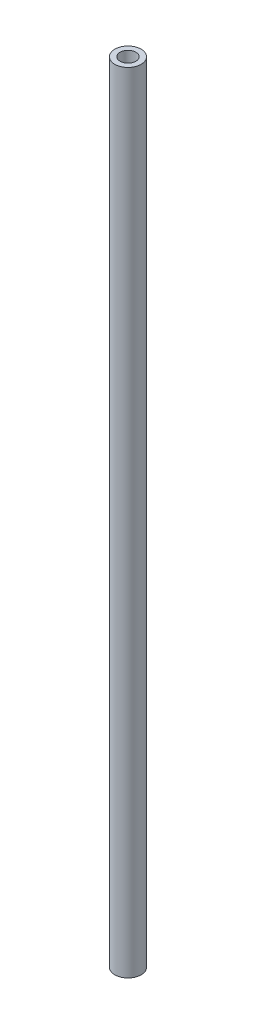
SolidWorks part; units mm, degrees
ref_plane "前视基准面" through (0, 0, 0) normal (0, 0, 1) x (1, 0, 0)
ref_plane "上视基准面" through (0, 0, 0) normal (0, 1, 0) x (1, 0, 0)
ref_plane "右视基准面" through (0, 0, 0) normal (1, 0, 0) x (0, 0, -1)
sketch "草图2" plane through (0, 0, 0) normal (0, 1, 0) x (1, 0, 0)
  circle A0 centre (0, 0) radius 5
  dimension "D1" = 10
extrude "凸台-拉伸1" add sketch "草图2" along normal mid plane 300
sketch "草图3" plane through (0, 0, 0) normal (0, 0, 1) x (1, 0, 0)
  line L0 (5, 150) -> (-5, 150) construction
  line L1 (0, 157.5) -> (0, 142.5)
  arc A0 (0, 142.5) -> (0, 157.5) centre (0, 150) ccw
  dimension "D1" = 15
sketch "草图4" plane through (0, 150, 0) normal (0, 1, 0) x (1, 0, 0)
  circle A0 centre (0, 0) radius 3
  dimension "D1" = 6
extrude "切除-拉伸1" cut sketch "草图4" against normal through all
